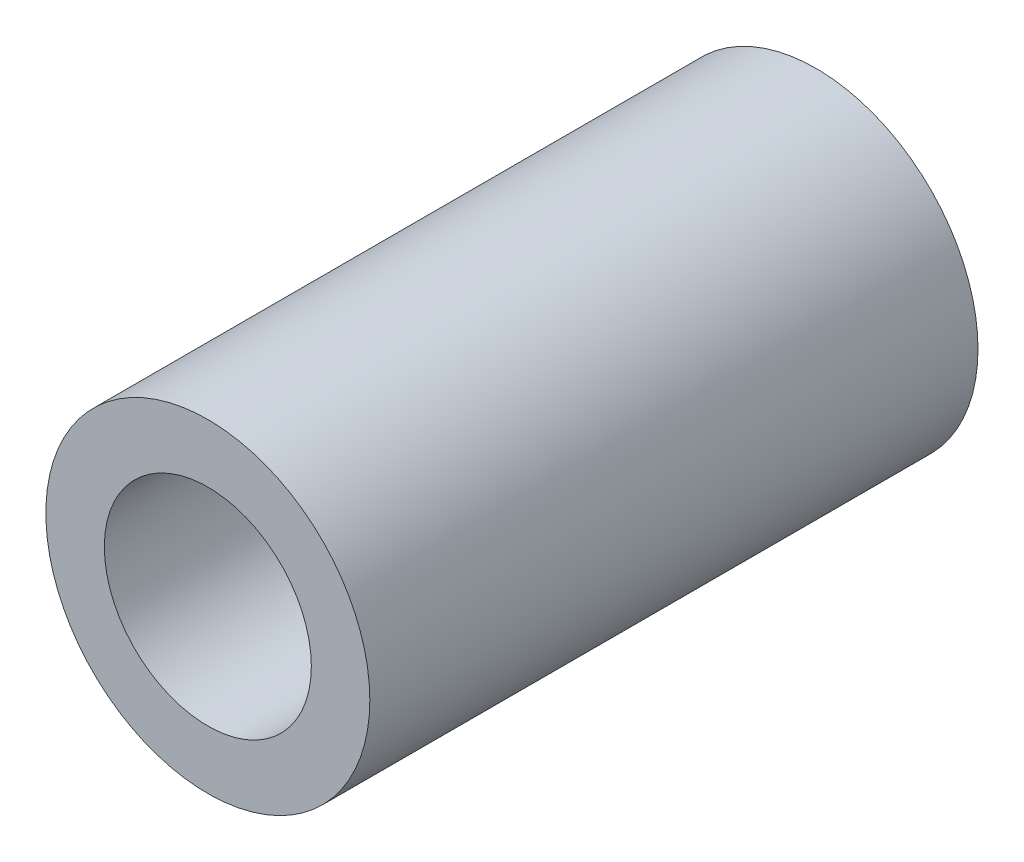
SolidWorks part; units mm, degrees
material "사용자정의 플라스틱"
ref_plane "정면" through (0, 0, 0) normal (0, 0, 1) x (1, 0, 0)
ref_plane "윗면" through (0, 0, 0) normal (0, 1, 0) x (1, 0, 0)
ref_plane "우측면" through (0, 0, 0) normal (1, 0, 0) x (0, 0, -1)
sketch "스케치1" plane through (0, 0, 0) normal (0, 0, 1) x (1, 0, 0)
  circle A0 centre (0, 0) radius 3.54
  circle A1 centre (0, 0) radius 5.54
  dimension "D1" = 7.08
  dimension "D2" = 2
extrude "보스-돌출1" add sketch "스케치1" along normal blind 20.8 contours A1 A0
